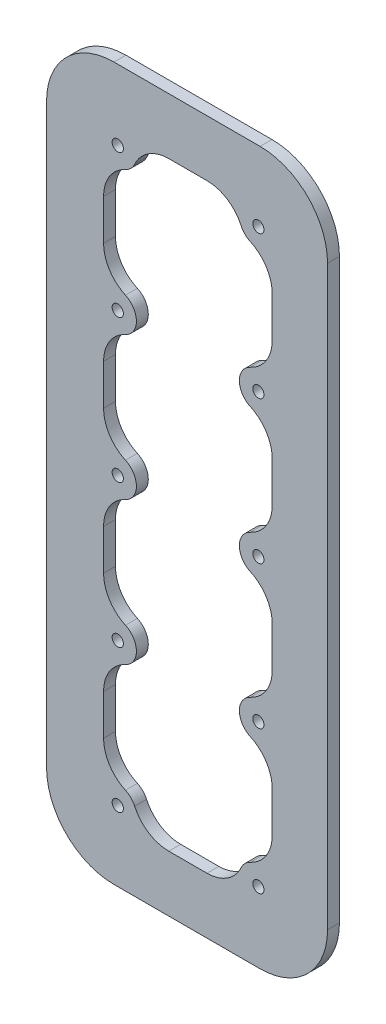
SolidWorks part; units mm, degrees
ref_plane "Front Plane" through (0, 0, 0) normal (0, 0, 1) x (1, 0, 0)
ref_plane "Top Plane" through (0, 0, 0) normal (0, 1, 0) x (1, 0, 0)
ref_plane "Right Plane" through (0, 0, 0) normal (1, 0, 0) x (0, 0, -1)
sketch "Sketch1" plane through (0, 0, 0) normal (0, 0, 1) x (1, 0, 0)
  line L4 (-5.9073, -79.0069) -> (-5.9073, 74.9931)
  line L5 (-62.8726, -97.0069) -> (-23.8963, -97.0069)
  line L6 (-80.8616, 74.9931) -> (-80.8616, -79.0069)
  line L7 (-23.8963, 92.9931) -> (-62.8726, 92.9931)
  line L8 (-5.9073, -79.0069) -> (-5.9073, 74.9931)
  line L9 (-62.8726, -97.0069) -> (-23.8963, -97.0069)
  line L10 (-80.8616, 74.9931) -> (-80.8616, -79.0069)
  line L11 (-23.8963, 92.9931) -> (-62.8726, 92.9931)
  ellipse E4 centre (-23.8963, -79.0069) end of major axis (-23.8963, -97.0069) minor radius 17.989 (-23.8963, -97.0069) -> (-5.9073, -79.0069) ccw
  ellipse E5 centre (-62.8726, -79.0069) end of major axis (-62.8726, -61.0069) minor radius 17.989 (-80.8616, -79.0069) -> (-62.8726, -97.0069) ccw
  ellipse E6 centre (-62.8726, 74.9931) end of major axis (-62.8726, 92.9931) minor radius 17.989 (-62.8726, 92.9931) -> (-80.8616, 74.9931) ccw
  ellipse E7 centre (-23.8963, 74.9931) end of major axis (-23.8963, 92.9931) minor radius 17.989 (-5.9073, 74.9931) -> (-23.8963, 92.9931) ccw
  ellipse E8 centre (-23.8963, -79.0069) end of major axis (-23.8963, -97.0069) minor radius 17.989 (-23.8963, -97.0069) -> (-5.9073, -79.0069) ccw
  ellipse E9 centre (-62.8726, -79.0069) end of major axis (-62.8726, -61.0069) minor radius 17.989 (-80.8616, -79.0069) -> (-62.8726, -97.0069) ccw
  ellipse E10 centre (-62.8726, 74.9931) end of major axis (-62.8726, 92.9931) minor radius 17.989 (-62.8726, 92.9931) -> (-80.8616, 74.9931) ccw
  ellipse E11 centre (-23.8963, 74.9931) end of major axis (-23.8963, 92.9931) minor radius 17.989 (-5.9073, 74.9931) -> (-23.8963, 92.9931) ccw
  dimension "D1" = 0
extrude "Boss-Extrude1" add sketch "Sketch1" along normal blind 3.175
sketch "Sketch2" plane through (0, 0, 3.175) normal (0, 0, 1) x (1, 0, 0)
  line L30 (-20.6765, 41.1144) -> (-20.6765, 69.2357)
  line L31 (-24.4316, 41.1144) -> (-20.6765, 41.1144)
  line L32 (-20.6765, 31.1144) -> (-24.4316, 31.1144)
  line L33 (-20.6765, 2.9931) -> (-20.6765, 31.1144)
  line L34 (-24.4316, 2.9931) -> (-20.6765, 2.9931)
  line L35 (-20.6765, -7.0069) -> (-24.4316, -7.0069)
  line L36 (-20.6765, -35.1283) -> (-20.6765, -7.0069)
  line L37 (-24.4316, -35.1283) -> (-20.6765, -35.1283)
  line L38 (-20.6765, -45.1283) -> (-24.4316, -45.1283)
  line L39 (-20.6765, -73.2496) -> (-20.6765, -45.1283)
  line L40 (-24.4316, -73.2496) -> (-20.6765, -73.2496)
  line L41 (-29.6502, -82.0069) -> (-29.4286, -78.2496)
  line L42 (-56.8971, -82.0069) -> (-29.6502, -82.0069)
  line L43 (-56.8971, -78.2496) -> (-56.8971, -82.0069)
  line L44 (-65.6491, -73.2496) -> (-61.8941, -73.2496)
  line L45 (-65.6491, -45.1283) -> (-65.6491, -73.2496)
  line L46 (-61.8941, -45.1283) -> (-65.6491, -45.1283)
  line L47 (-65.6491, -35.1283) -> (-61.8941, -35.1283)
  line L48 (-65.6491, -7.0069) -> (-65.6491, -35.1283)
  line L49 (-61.8941, -7.0069) -> (-65.6491, -7.0069)
  line L50 (-65.6491, 2.9931) -> (-61.8941, 2.9931)
  line L51 (-65.6491, 31.1144) -> (-65.6491, 2.9931)
  line L52 (-61.8941, 31.1144) -> (-65.6491, 31.1144)
  line L53 (-65.6491, 41.1144) -> (-61.8941, 41.1144)
  line L54 (-65.6491, 69.2357) -> (-65.6491, 41.1144)
  line L55 (-61.8941, 69.2357) -> (-65.6491, 69.2357)
  line L56 (-56.8971, 77.9931) -> (-56.8971, 74.2357)
  line L57 (-29.6502, 77.9931) -> (-56.8971, 77.9931)
  line L58 (-29.4286, 74.2357) -> (-29.6502, 77.9931)
  line L59 (-20.6765, 69.2357) -> (-24.4316, 69.2357)
  line L60 (-20.6765, 41.1144) -> (-20.6765, 69.2357)
  line L61 (-24.4316, 41.1144) -> (-20.6765, 41.1144)
  line L62 (-20.6765, 31.1144) -> (-24.4316, 31.1144)
  line L63 (-20.6765, 2.9931) -> (-20.6765, 31.1144)
  line L64 (-24.4316, 2.9931) -> (-20.6765, 2.9931)
  line L65 (-20.6765, -7.0069) -> (-24.4316, -7.0069)
  line L66 (-20.6765, -35.1283) -> (-20.6765, -7.0069)
  line L67 (-24.4316, -35.1283) -> (-20.6765, -35.1283)
  line L68 (-20.6765, -45.1283) -> (-24.4316, -45.1283)
  line L69 (-20.6765, -73.2496) -> (-20.6765, -45.1283)
  line L70 (-24.4316, -73.2496) -> (-20.6765, -73.2496)
  line L71 (-29.6502, -82.0069) -> (-29.4286, -78.2496)
  line L72 (-56.8971, -82.0069) -> (-29.6502, -82.0069)
  line L73 (-56.8971, -78.2496) -> (-56.8971, -82.0069)
  line L74 (-65.6491, -73.2496) -> (-61.8941, -73.2496)
  line L75 (-65.6491, -45.1283) -> (-65.6491, -73.2496)
  line L76 (-61.8941, -45.1283) -> (-65.6491, -45.1283)
  line L77 (-65.6491, -35.1283) -> (-61.8941, -35.1283)
  line L78 (-65.6491, -7.0069) -> (-65.6491, -35.1283)
  line L79 (-61.8941, -7.0069) -> (-65.6491, -7.0069)
  line L80 (-65.6491, 2.9931) -> (-61.8941, 2.9931)
  line L81 (-65.6491, 31.1144) -> (-65.6491, 2.9931)
  line L82 (-61.8941, 31.1144) -> (-65.6491, 31.1144)
  line L83 (-65.6491, 41.1144) -> (-61.8941, 41.1144)
  line L84 (-65.6491, 69.2357) -> (-65.6491, 41.1144)
  line L85 (-61.8941, 69.2357) -> (-65.6491, 69.2357)
  line L86 (-56.8971, 77.9931) -> (-56.8971, 74.2357)
  line L87 (-29.6502, 77.9931) -> (-56.8971, 77.9931)
  line L88 (-29.4286, 74.2357) -> (-29.6502, 77.9931)
  line L89 (-20.6765, 69.2357) -> (-24.4316, 69.2357)
  circle A1 centre (-61.8613, 74.2357) radius 1.5
  circle A2 centre (-61.8613, 74.2357) radius 1.5
  circle A3 centre (-24.3532, 74.2357) radius 1.5
  circle A4 centre (-24.3532, 74.2357) radius 1.5
  circle A5 centre (-24.3532, 36.1144) radius 1.5
  circle A6 centre (-24.3532, 36.1144) radius 1.5
  circle A7 centre (-24.3532, -2.0069) radius 1.5
  circle A8 centre (-24.3532, -2.0069) radius 1.5
  circle A9 centre (-24.3532, -40.1283) radius 1.5
  circle A10 centre (-24.3532, -40.1283) radius 1.5
  circle A11 centre (-61.8613, -40.1283) radius 1.5
  circle A12 centre (-61.8613, -40.1283) radius 1.5
  circle A13 centre (-61.8613, -2.0069) radius 1.5
  circle A14 centre (-61.8613, -2.0069) radius 1.5
  circle A15 centre (-61.8613, 36.1144) radius 1.5
  circle A16 centre (-61.8613, 36.1144) radius 1.5
  circle A17 centre (-24.3532, -78.2496) radius 1.5
  circle A18 centre (-24.3532, -78.2496) radius 1.5
  circle A19 centre (-61.8613, -78.2496) radius 1.5
  circle A20 centre (-61.8613, -78.2496) radius 1.5
  ellipse E10 centre (-24.4316, 36.1144) end of major axis (-24.4316, 41.1144) minor radius 4.997 (-24.4316, 41.1144) -> (-24.4316, 31.1144) ccw
  ellipse E11 centre (-24.4316, -2.0069) end of major axis (-24.4316, -7.0069) minor radius 4.997 (-24.4316, 2.9931) -> (-24.4316, -7.0069) ccw
  ellipse E12 centre (-24.4316, -40.1283) end of major axis (-24.4316, -35.1283) minor radius 4.997 (-24.4316, -35.1283) -> (-24.4316, -45.1283) ccw
  ellipse E13 centre (-24.4316, -78.2496) end of major axis (-24.4316, -73.2496) minor radius 4.997 (-24.4316, -73.2496) -> (-29.4286, -78.2496) ccw
  ellipse E14 centre (-61.8941, -78.2496) end of major axis (-61.8941, -83.2496) minor radius 4.997 (-56.8971, -78.2496) -> (-61.8941, -73.2496) ccw
  ellipse E15 centre (-61.8941, -40.1283) end of major axis (-61.8941, -45.1283) minor radius 4.997 (-61.8941, -45.1283) -> (-61.8941, -35.1283) ccw
  ellipse E16 centre (-61.8941, -2.0069) end of major axis (-61.8941, -7.0069) minor radius 4.997 (-61.8941, -7.0069) -> (-61.8941, 2.9931) ccw
  ellipse E17 centre (-61.8941, 36.1144) end of major axis (-61.8941, 31.1144) minor radius 4.997 (-61.8941, 31.1144) -> (-61.8941, 41.1144) ccw
  ellipse E18 centre (-61.8941, 74.2357) end of major axis (-61.8941, 69.2357) minor radius 4.997 (-61.8941, 69.2357) -> (-56.8971, 74.2357) ccw
  ellipse E19 centre (-24.4316, 74.2357) end of major axis (-24.4316, 79.2357) minor radius 4.997 (-29.4286, 74.2357) -> (-24.4316, 69.2357) ccw
  ellipse E20 centre (-24.4316, 36.1144) end of major axis (-24.4316, 41.1144) minor radius 4.997 (-24.4316, 41.1144) -> (-24.4316, 31.1144) ccw
  ellipse E21 centre (-24.4316, -2.0069) end of major axis (-24.4316, -7.0069) minor radius 4.997 (-24.4316, 2.9931) -> (-24.4316, -7.0069) ccw
  ellipse E22 centre (-24.4316, -40.1283) end of major axis (-24.4316, -35.1283) minor radius 4.997 (-24.4316, -35.1283) -> (-24.4316, -45.1283) ccw
  ellipse E23 centre (-24.4316, -78.2496) end of major axis (-24.4316, -73.2496) minor radius 4.997 (-24.4316, -73.2496) -> (-29.4286, -78.2496) ccw
  ellipse E24 centre (-61.8941, -78.2496) end of major axis (-61.8941, -83.2496) minor radius 4.997 (-56.8971, -78.2496) -> (-61.8941, -73.2496) ccw
  ellipse E25 centre (-61.8941, -40.1283) end of major axis (-61.8941, -45.1283) minor radius 4.997 (-61.8941, -45.1283) -> (-61.8941, -35.1283) ccw
  ellipse E26 centre (-61.8941, -2.0069) end of major axis (-61.8941, -7.0069) minor radius 4.997 (-61.8941, -7.0069) -> (-61.8941, 2.9931) ccw
  ellipse E27 centre (-61.8941, 36.1144) end of major axis (-61.8941, 31.1144) minor radius 4.997 (-61.8941, 31.1144) -> (-61.8941, 41.1144) ccw
  ellipse E28 centre (-61.8941, 74.2357) end of major axis (-61.8941, 69.2357) minor radius 4.997 (-61.8941, 69.2357) -> (-56.8971, 74.2357) ccw
  ellipse E29 centre (-24.4316, 74.2357) end of major axis (-24.4316, 79.2357) minor radius 4.997 (-29.4286, 74.2357) -> (-24.4316, 69.2357) ccw
  dimension "D1" = 0
  dimension "D2" = 0
  dimension "D3" = 0
  dimension "D4" = 0
  dimension "D5" = 0
  dimension "D6" = 0
  dimension "D7" = 0
  dimension "D8" = 0
  dimension "D9" = 0
  dimension "D10" = 0
  dimension "D11" = 0
extrude "Cut-Extrude1" cut sketch "Sketch2" against normal through all
fillet "Fillet1" radius 10 20 edges at (-20.6765, 41.1144, 1.5875) (-20.6765, 2.9931, 1.5875) (-20.6765, -35.1283, 1.5875) (-29.6502, -82.0069, 1.5875) (-20.6765, -73.2496, 1.5875) (-20.6765, -7.0069, 1.5875) (-20.6765, -45.1283, 1.5875) (-20.6765, 31.1144, 1.5875) (-20.6765, 69.2357, 1.5875) (-29.6502, 77.9931, 1.5875) (-65.6491, 41.1144, 1.5875) (-65.6491, 2.9931, 1.5875) (-65.6491, -35.1283, 1.5875) (-56.8971, -82.0069, 1.5875) (-65.6491, -73.2496, 1.5875) (-65.6491, -7.0069, 1.5875) (-65.6491, -45.1283, 1.5875) (-65.6491, 31.1144, 1.5875) (-56.8971, 77.9931, 1.5875) (-65.6491, 69.2357, 1.5875)
